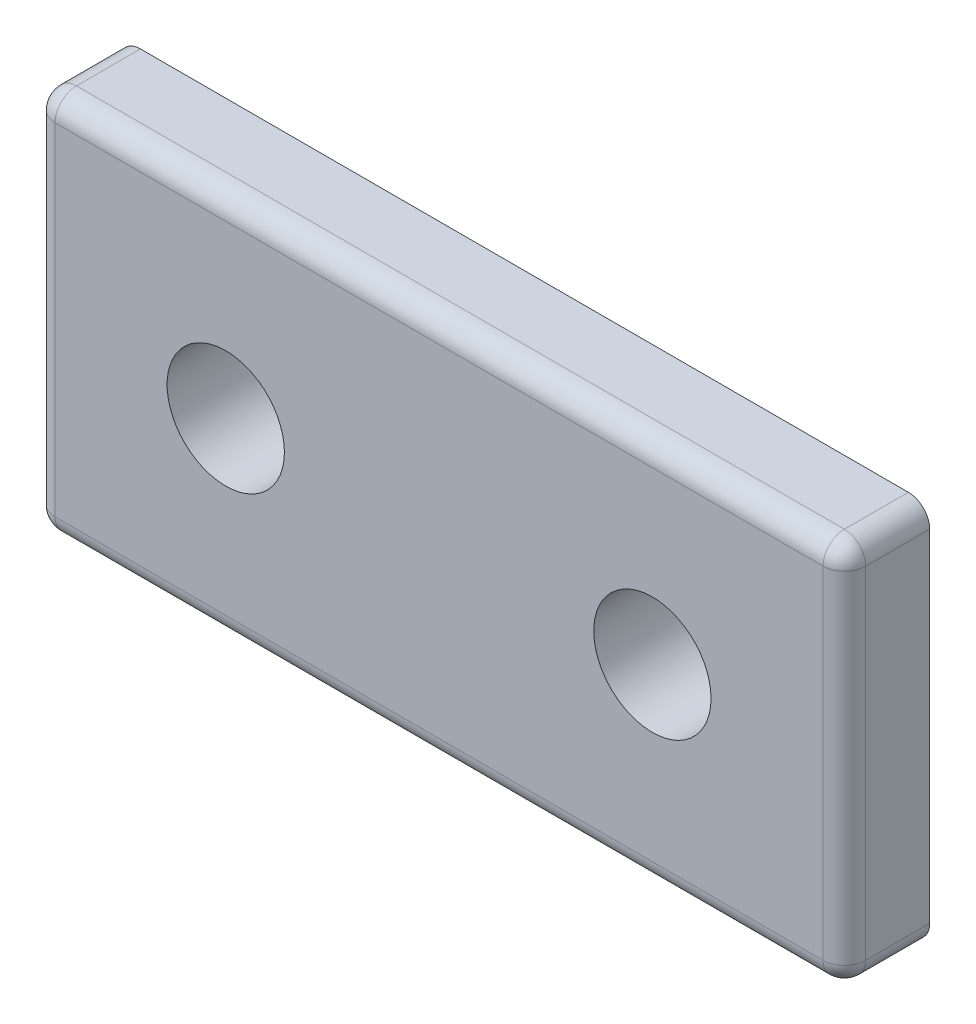
SolidWorks part; units mm, degrees
ref_plane "Front Plane" through (0, 0, 0) normal (0, 0, 1) x (1, 0, 0)
ref_plane "Top Plane" through (0, 0, 0) normal (0, 1, 0) x (1, 0, 0)
ref_plane "Right Plane" through (0, 0, 0) normal (1, 0, 0) x (0, 0, -1)
sketch "Sketch1" plane through (0, 0, 0) normal (0, 0, 1) x (1, 0, 0)
  line L0 (0, 0) -> (0, 18)
  line L1 (9, 9) -> (29, 9) construction
  line L4 (38, 18) -> (0, 18)
  line L5 (38, 0) -> (0, 0)
  line L7 (38, 18) -> (38, 0)
  circle A0 centre (9, 9) radius 2.75
  circle A1 centre (29, 9) radius 2.75
  dimension "D1" = 20
  dimension "E" = 5.5
  dimension "D2" = 9
  dimension "C" = 18
  dimension "D3" = 9
  dimension "B" = 38
extrude "Boss-Extrude1" add sketch "Sketch1" along normal mid plane 4
fillet "Fillet1" radius 1 8 edges at (0, 0, 0) (0, 9, 2) (19, 0, 2) (38, 9, 2) (38, 0, 0) (38, 18, 0) (19, 18, 2) (0, 18, 0)
